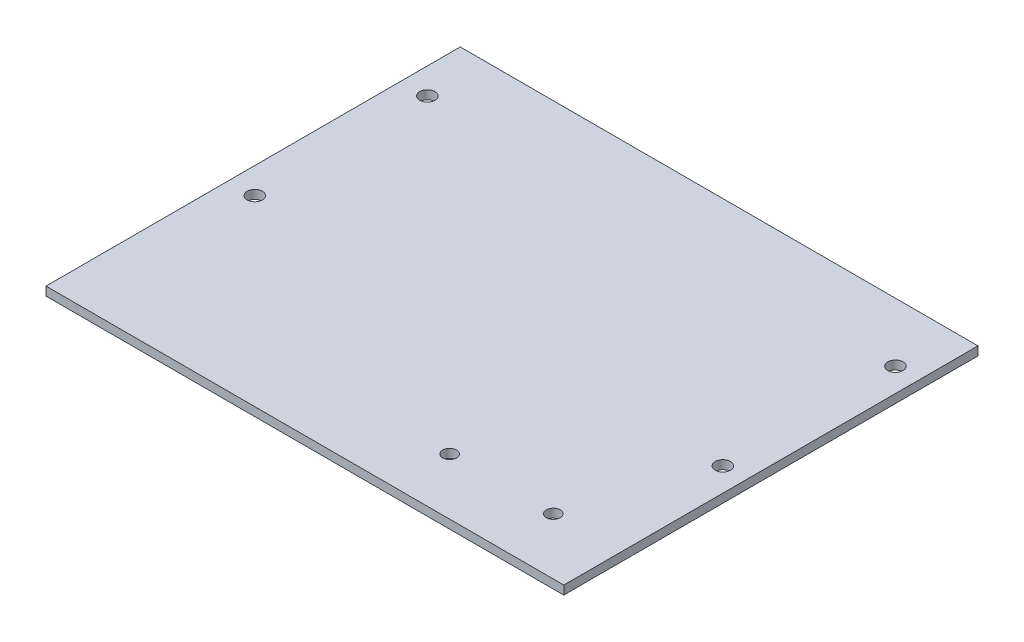
SolidWorks part; units mm, degrees
ref_plane "Front Plane" through (0, 0, 0) normal (0, 0, 1) x (1, 0, 0)
ref_plane "Top Plane" through (0, 0, 0) normal (0, 1, 0) x (1, 0, 0)
ref_plane "Right Plane" through (0, 0, 0) normal (1, 0, 0) x (0, 0, -1)
sketch "Sketch1" plane through (0, 0, 0) normal (0, 1, 0) x (1, 0, 0)
  line L1 (-46.2594, 47.9664) -> (48.9906, 47.9664)
  line L2 (-46.2594, 47.9664) -> (-46.2594, -28.2336)
  line L3 (-46.2594, -28.2336) -> (48.9906, -28.2336)
  line L4 (48.9906, 47.9664) -> (48.9906, -28.2336)
  dimension "D1" = 95.25
  dimension "D2" = 76.2
extrude "Boss-Extrude1" add sketch "Sketch1" along normal blind 1.6
sketch "Sketch2" plane through (0, 1.6, 0) normal (0, 1, 0) x (1, 0, 0)
  circle A0 centre (-41.4715, 37.1333) radius 1.397
  dimension "D1" = 2.794
extrude "Cut-Extrude1" cut sketch "Sketch2" against normal through all
pattern_linear "LPattern1" count 2 spacing 86.106 along (1, 0, 0) count 2 spacing 31.75 along (0, 0, 1) of "Cut-Extrude1"
sketch "Sketch4" plane through (0, 1.6, 0) normal (0, 1, 0) x (1, 0, 0)
  circle A0 centre (17.6136, -17.8572) radius 1.27
  dimension "D1" = 2.54
extrude "Cut-Extrude2" cut sketch "Sketch4" against normal through all
pattern_linear "LPattern2" count 2 spacing 19.05 along (1, 0, 0) of "Cut-Extrude2"
